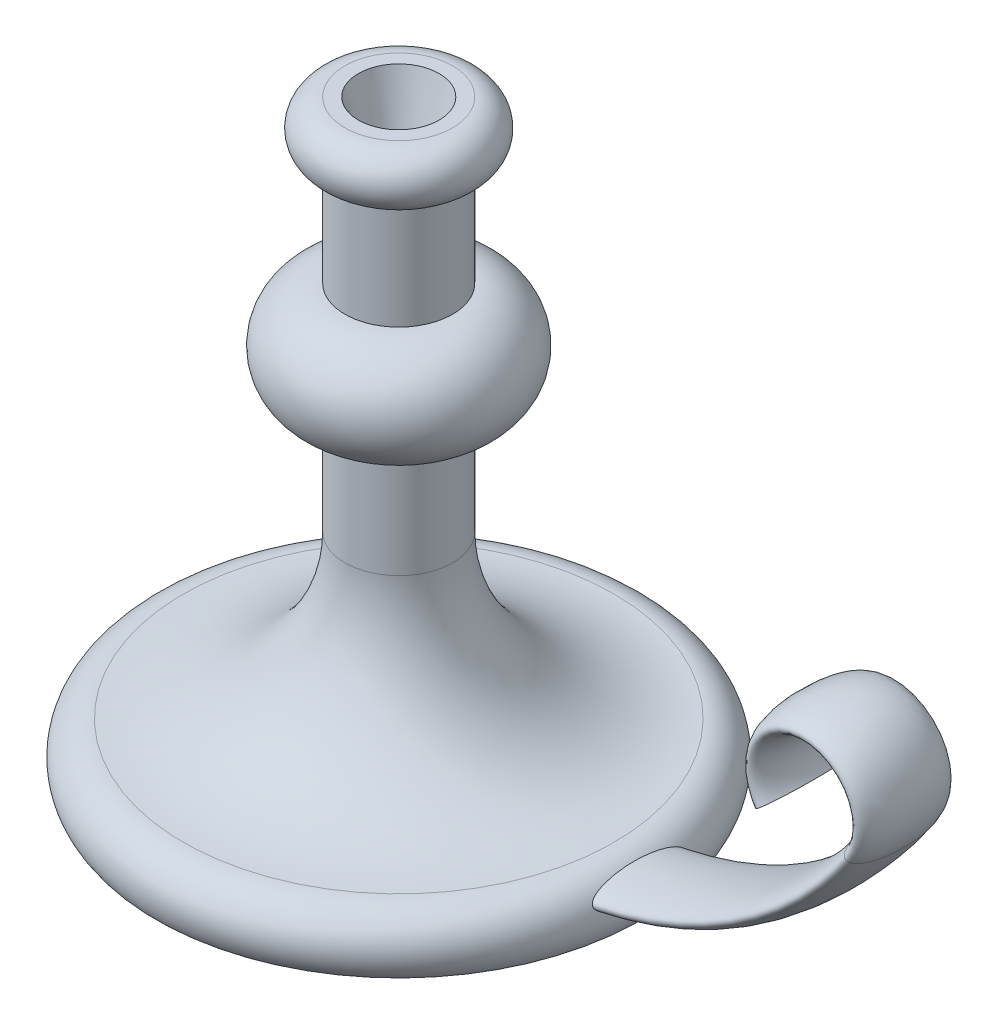
SolidWorks part; units mm, degrees
ref_plane "Front" through (0, 0, 0) normal (0, 0, 1) x (1, 0, 0)
ref_plane "Top" through (0, 0, 0) normal (0, 1, 0) x (1, 0, 0)
ref_plane "Right" through (0, 0, 0) normal (1, 0, 0) x (0, 0, -1)
sketch "Sketch1" plane through (0, 0, 0) normal (0, 0, 1) x (1, 0, 0)
  line L0 (0, 0) -> (0, 220)
  line L1 (0, 220) -> (20, 220)
  line L2 (0, 0) -> (90, 0)
  line L3 (20, 200) -> (20, 160)
  line L4 (20, 120) -> (20, 80)
  arc A0 (20, 220) -> (20, 200) centre (20, 210) cw
  arc A1 (20, 160) -> (20, 120) centre (20, 140) cw
  arc A2 (20, 80) -> (80, 20) centre (80, 80) ccw
  arc A3 (80, 20) -> (90, 0) centre (80, 7.5) cw
  dimension "D4" = 10
  dimension "D5" = 20
  dimension "D8" = 60
  dimension "D9" = 12.5
  dimension "D1" = 220
  dimension "D2" = 20
  dimension "D3" = 90
  dimension "D6" = 40
  dimension "D7" = 80
revolve "Revolve1" add sketch "Sketch1" angle 360 about L0
sketch "Sketch2" plane through (0, 0, 0) normal (0, 0, 1) x (1, 0, 0)
  line L0 (0, 10) -> (60, 10)
  line L1 (0, 227.4356) -> (0, 175.1288) construction
  line L2 (0, 200) -> (0, 160) construction
  arc A0 (60, 10) -> (183.5921, 75) centre (60, 160) ccw
  arc A1 (183.5921, 75) -> (150.6342, 75) centre (167.1131, 86.3333) ccw
  dimension "D3" = 150
  dimension "D4" = 20
  dimension "D1" = 60
  dimension "D2" = 65
  dimension "D5" = 10
sketch "Sketch3" plane through (0, 0, 0) normal (1, 0, 0) x (0, 0, -1)
  ellipse E0 centre (0, 10) end of major axis (-17.5, 10) minor radius 5
  dimension "D1" = 35
  dimension "D2" = 10
sweep "Sweep1" add profiles "Sketch3" path "Sketch2"
sketch "Sketch4" plane through (0, 220, 0) normal (0, 1, 0) x (1, 0, 0)
  circle A0 centre (0, 0) radius 15
  dimension "D1" = 30
extrude "Cut-Extrude2" cut sketch "Sketch4" against normal blind 25 draft 15
